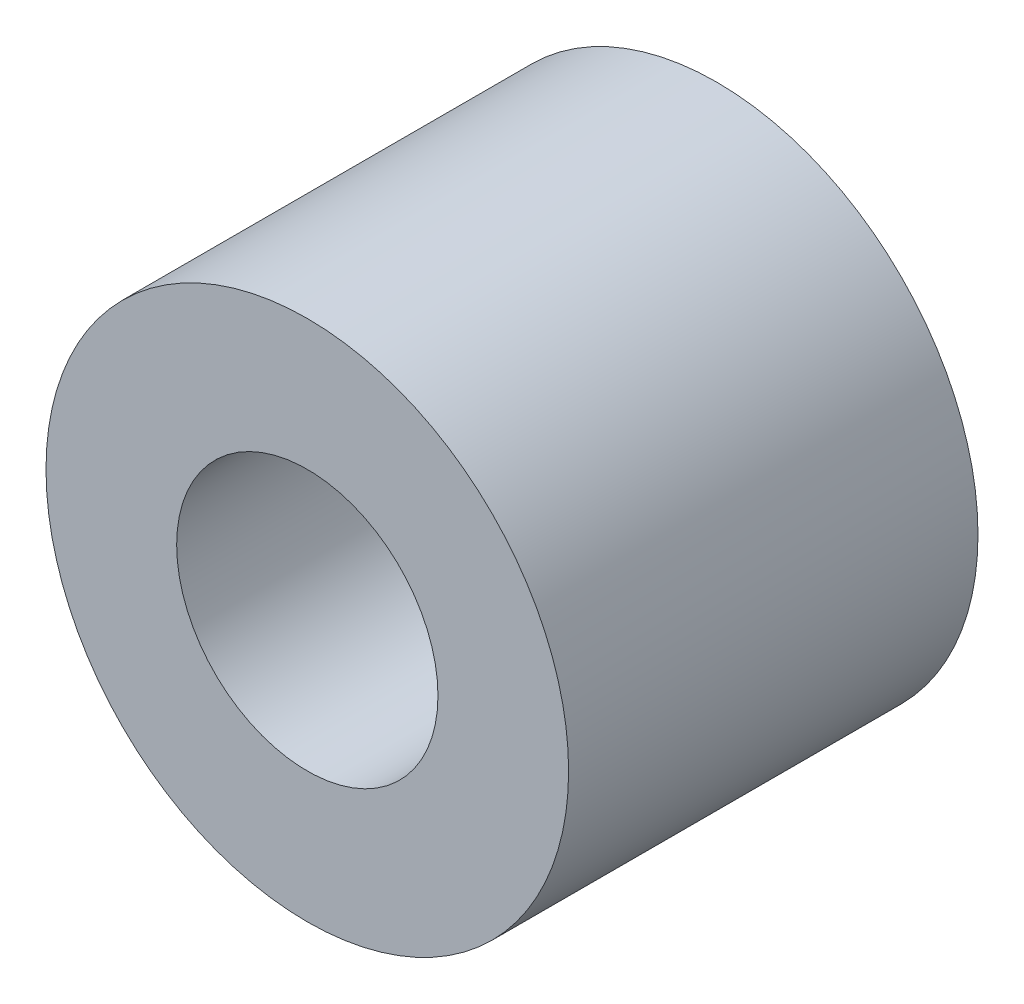
SolidWorks part; units mm, degrees
ref_plane "Front Plane" through (0, 0, 0) normal (0, 0, 1) x (1, 0, 0)
ref_plane "Top Plane" through (0, 0, 0) normal (0, 1, 0) x (1, 0, 0)
ref_plane "Right Plane" through (0, 0, 0) normal (1, 0, 0) x (0, 0, -1)
sketch "Sketch1" plane through (0, 0, 0) normal (0, 0, 1) x (1, 0, 0)
  circle A0 centre (-46, 0) radius 1.5
  circle A1 centre (-46, 0) radius 3
  dimension "D1" = 3
extrude "Boss-Extrude1" add sketch "Sketch1" against normal up to surface (4.7 mm away)
